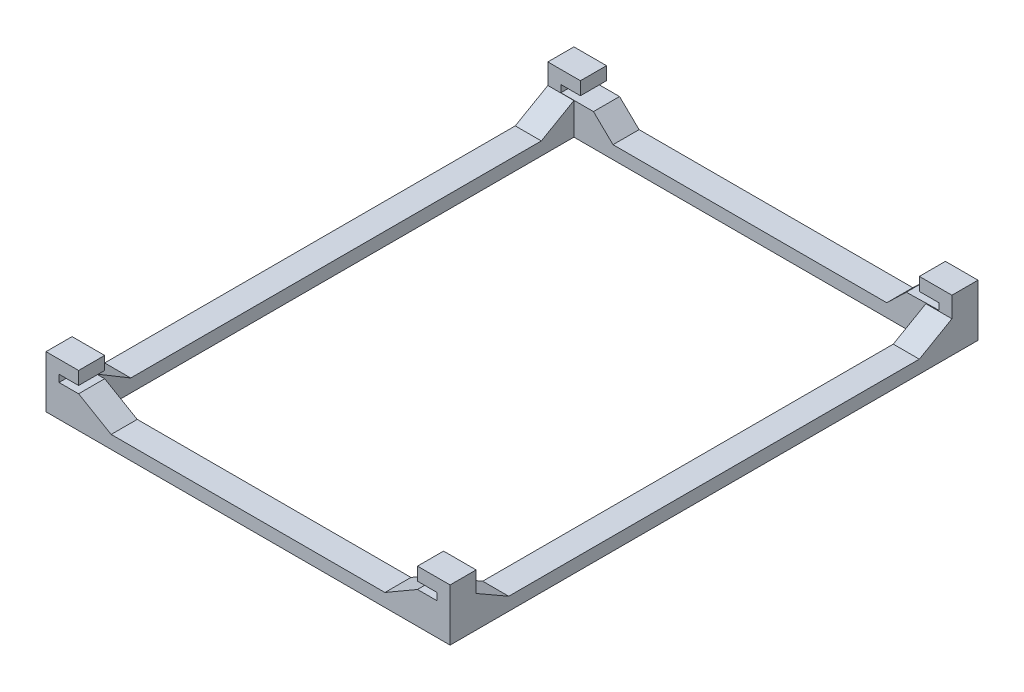
SolidWorks part; units mm, degrees
ref_plane "Спереди" through (0, 0, 0) normal (0, 0, 1) x (1, 0, 0)
ref_plane "Сверху" through (0, 0, 0) normal (0, 1, 0) x (1, 0, 0)
ref_plane "Справа" through (0, 0, 0) normal (1, 0, 0) x (0, 0, -1)
other "Configuration Table"
sketch "Эскиз1" plane through (0, 0, 0) normal (0, 1, 0) x (1, 0, 0)
  line L1 (31, -40.5) -> (-31, -40.5)
  line L2 (31, -40.5) -> (31, 40.5)
  line L3 (31, 40.5) -> (-31, 40.5)
  line L4 (-31, -40.5) -> (-31, 40.5)
  line L5 (31, -40.5) -> (-31, 40.5) construction
  line L6 (31, 40.5) -> (-31, -40.5) construction
  line L7 (27, -36.5) -> (-27, -36.5)
  line L8 (27, -36.5) -> (27, 36.5)
  line L9 (27, 36.5) -> (-27, 36.5)
  line L10 (-27, -36.5) -> (-27, 36.5)
  line L11 (27, -36.5) -> (-27, 36.5) construction
  line L12 (27, 36.5) -> (-27, -36.5) construction
  point P0 (0, 0)
  point P6 (0, 0)
  dimension "D1" = 62
  dimension "D2" = 81
  dimension "D3" = 54
  dimension "D4" = 73
extrude "Бобышка-Вытянуть1" add sketch "Эскиз1" along normal blind 2
sketch "Эскиз6" plane through (0, 0, 40.5) normal (0, 0, 1) x (1, 0, 0)
  line L0 (31, 2) -> (31, 8)
  line L1 (31, 8) -> (26, 8)
  line L2 (26, 8) -> (26, 6)
  line L3 (26, 6) -> (29, 6)
  line L4 (29, 6) -> (29, 4.9)
  line L5 (29, 4.9) -> (26, 4.9)
  line L6 (26, 4.9) -> (26, 2)
  line L7 (-31, 2) -> (31, 2) construction
  line L8 (26, 2) -> (31, 2)
  line L9 (26, 4.9) -> (21, 2)
  line L10 (21, 2) -> (26, 2)
  line L11 (26, 4.9) -> (21, 2)
  line L12 (21, 2) -> (26, 4.9)
  line M14 (31, 2) -> (-31, 2)
  dimension "D1" = 6
  dimension "D2" = 5
  dimension "D3" = 3
  dimension "D4" = 3
  dimension "D5" = 1.1
  dimension "D6" = 2
  dimension "D7" = 5
extrude "Бобышка-Вытянуть2" add sketch "Эскиз6" against normal blind 4 contours L5 L6 L0 L1 L2 L3 L4 M14 | L6 L9 M14
sketch "Эскиз8" plane through (0, 0, 40.5) normal (0, 0, 1) x (1, 0, 0)
  line L0 (-31, 2) -> (-31, 8)
  line L1 (-31, 8) -> (-26, 8)
  line L2 (-26, 8) -> (-26, 6)
  line L3 (-26, 6) -> (-29, 6)
  line L4 (-29, 6) -> (-29, 4.9)
  line L5 (-29, 4.9) -> (-26, 4.9)
  line L6 (-26, 4.9) -> (-26, 2)
  line L7 (-31, 2) -> (21, 2) construction
  line L8 (-26, 2) -> (-21, 2)
  line L9 (-21, 2) -> (-26, 4.9)
  line M16 (21, 2) -> (-31, 2)
  dimension "D1" = 6
  dimension "D2" = 5
  dimension "D3" = 1.1
  dimension "D4" = 2
  dimension "D5" = 5
  dimension "D6" = 3
  dimension "D7" = 3
extrude "Бобышка-Вытянуть3" add sketch "Эскиз8" against normal blind 4 contours L6 L5 L4 L3 L2 L1 L0 M16 | L9 L6 M16
sketch "Эскиз10" plane through (0, 0, -40.5) normal (0, 0, -1) x (-1, 0, 0)
  line L0 (-31, 2) -> (-31, 8)
  line L1 (-31, 8) -> (-26, 8)
  line L2 (-26, 8) -> (-26, 6)
  line L3 (-26, 6) -> (-29, 6)
  line L4 (-29, 6) -> (-29, 5)
  line L5 (-29, 5) -> (-24, 4.9)
  line L6 (-29, 4.9) -> (-26, 4.9) construction
  line L7 (-24, 4.9) -> (-24, 2)
  line L8 (-31, 2) -> (31, 2) construction
  line L9 (-24, 2) -> (-31, 2)
  line L10 (-21, 2) -> (-24, 4.9)
  line L11 (-24, 2) -> (-21, 2)
  line M4 (31, 2) -> (-31, 2)
  dimension "D1" = 5
extrude "Бобышка-Вытянуть4" add sketch "Эскиз10" against normal blind 4 contours L7 L5 L4 L3 L2 L1 L0 M4 | L10 L7 M4
sketch "Эскиз11" plane through (0, 0, -40.5) normal (0, 0, -1) x (-1, 0, 0)
  line L0 (31, 2) -> (31, 8)
  line L1 (31, 8) -> (26, 8)
  line L2 (26, 8) -> (26, 6)
  line L3 (26, 6) -> (29, 6)
  line L4 (29, 6) -> (29, 4.9)
  line L5 (29, 4.9) -> (24, 4.9)
  line L6 (29, 4.9) -> (26, 4.9) construction
  line L7 (24, 4.9) -> (24, 2)
  line L8 (-21, 2) -> (31, 2) construction
  line L9 (24, 2) -> (31, 2)
  line L10 (24, 4.9) -> (21, 2)
  line L11 (21, 2) -> (24, 2)
  line M3 (31, 2) -> (-21, 2)
extrude "Бобышка-Вытянуть5" add sketch "Эскиз11" against normal blind 4 contours L5 L7 L0 L1 L2 L3 L4 M3 | L7 L10 M3
sketch "Эскиз12" plane through (-31, 0, 0) normal (-1, 0, 0) x (0, 0, 1)
  line L0 (-36.5, 2) -> (-31.5, 2)
  line L1 (-36.5, 2) -> (36.5, 2) construction
  line L2 (-31.5, 2) -> (-36.5, 4.8667)
  line L3 (-36.5, 2) -> (-36.5, 8) construction
  line L4 (-36.5, 4.8667) -> (-36.5, 2)
  dimension "D1" = 5
extrude "Бобышка-Вытянуть6" add sketch "Эскиз12" against normal blind 4
sketch "Эскиз13" plane through (-31, 0, 0) normal (-1, 0, 0) x (0, 0, 1)
  line L0 (75.1841, 8.9588) -> (40.5, 5)
  line L1 (40.5, 8) -> (40.5, 0) construction
  line L2 (40.5, 5) -> (36.5, 5)
  line L3 (36.5, 2) -> (36.5, 8) construction
  line L4 (36.5, 5) -> (31.5, 2)
  line L5 (-31.5, 2) -> (36.5, 2) construction
  line L6 (31.5, 2) -> (36.5, 2)
  line L7 (36.5, 2) -> (36.5, 5)
  line M2 (36.5, 2) -> (-31.5, 2)
  line M10 (36.5, 8) -> (36.5, 2)
  dimension "D1" = 5
extrude "Бобышка-Вытянуть7" add sketch "Эскиз13" against normal blind 4 contours L4 M10 M2
sketch "Эскиз16" plane through (0, 0, 40.5) normal (0, 0, 1) x (1, 0, 0)
  line L0 (31, 4.8356) -> (26, 4.9)
  line L1 (31, 8) -> (31, 0) construction
  line L2 (26, 4.9) -> (31, 4.8356)
sketch "Эскиз17" plane through (31, 0, 0) normal (1, 0, 0) x (0, 0, -1)
  line L0 (-40.5, 4.8678) -> (-36.5, 4.8678)
  line L1 (-40.5, 4.8356) -> (-40.5, 4.9) construction
  line L2 (-36.5, 2) -> (-36.5, 8) construction
  line L3 (-36.5, 4.8678) -> (-36.5, 2)
  line L4 (-36.5, 2) -> (-31.5, 2)
  line L5 (-36.5, 2) -> (36.5, 2) construction
  line L6 (-31.5, 2) -> (-36.5, 4.8678)
  line L7 (-36.5, 4.8678) -> (-36.5, 2)
  line L8 (-31.5, 2) -> (-36.5, 4.8678)
  line M6 (36.5, 2) -> (-36.5, 2)
  line M7 (-36.5, 2) -> (-36.5, 8)
  dimension "D1" = 5
extrude "Бобышка-Вытянуть8" add sketch "Эскиз17" against normal blind 4 contours L6 M6 M7
sketch "Эскиз20" plane through (0, 0, -40.5) normal (0, 0, -1) x (-1, 0, 0)
  line L0 (-31, 4.8356) -> (-24, 4.9)
  line L1 (-24, 4.9) -> (-31, 4.8356)
sketch "Эскиз21" plane through (31, 0, 0) normal (1, 0, 0) x (0, 0, -1)
  line L0 (40.5, 4.8678) -> (36.5, 4.8667)
  line L1 (40.5, 4.8356) -> (40.5, 4.9) construction
  line L2 (36.5, 4.8667) -> (36.5, 0) construction
  line L3 (31.5, 2) -> (36.5, 4.8667) construction
  line L4 (36.5, 4.8667) -> (36.5, 2)
  line L5 (36.5, 2) -> (31.5, 2)
  line L6 (31.5, 2) -> (36.5, 4.8667)
  line M2 (36.5, 2) -> (-31.5, 2)
  line M10 (36.5, 8) -> (36.5, 2)
extrude "Бобышка-Вытянуть9" add sketch "Эскиз21" against normal blind 4 contours L6 M2 M10
